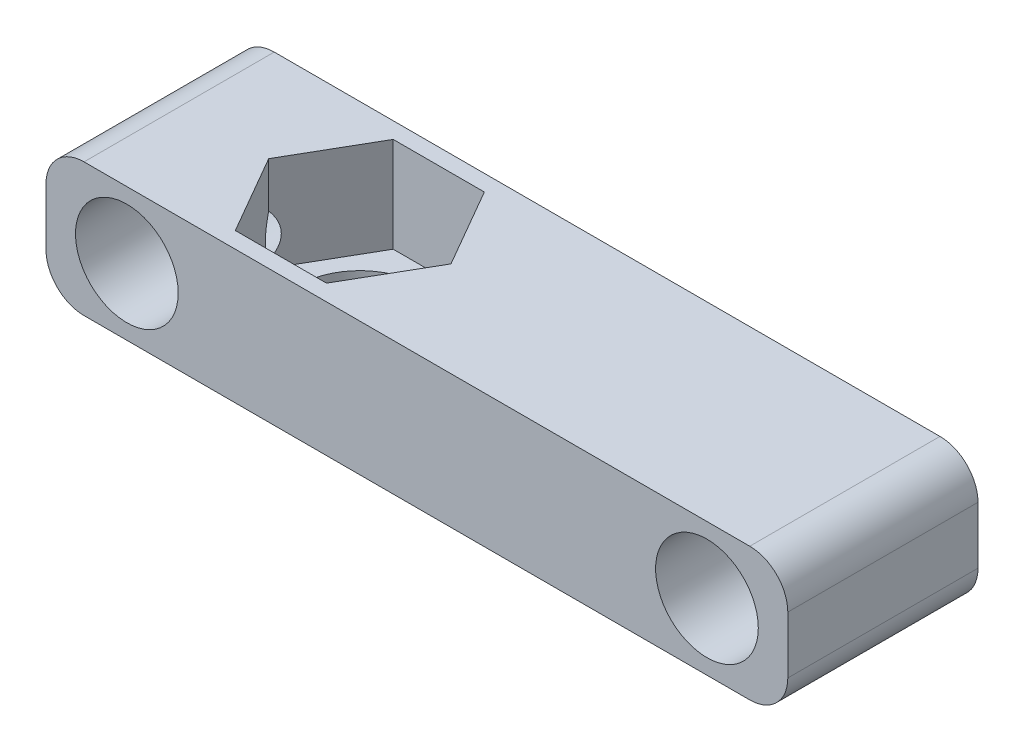
SolidWorks part; units mm, degrees
ref_plane "Alzado" through (0, 0, 0) normal (0, 0, 1) x (1, 0, 0)
ref_plane "Planta" through (0, 0, 0) normal (0, 1, 0) x (1, 0, 0)
ref_plane "Vista lateral" through (0, 0, 0) normal (1, 0, 0) x (0, 0, -1)
sketch "Croquis1" plane through (0, 0, 0) normal (0, 0, 1) x (1, 0, 0)
  line L1 (-46.0167, 15.878) -> (-7.0167, 15.878)
  line L2 (-46.0167, 15.878) -> (-46.0167, 8.878)
  line L3 (-46.0167, 8.878) -> (-7.0167, 8.878)
  line L4 (-7.0167, 15.878) -> (-7.0167, 8.878)
  circle A0 centre (-41.7667, 12.378) radius 2.7
  circle A1 centre (-11.2667, 12.378) radius 2.7
  dimension "D5" = 2
  dimension "D6" = 4.25
  dimension "D7" = 5.4
  dimension "D1" = 39
  dimension "D2" = 7
  dimension "D3" = 4.25
  dimension "D4" = 3.5
extrude "Saliente-Extruir1" add sketch "Croquis1" along normal blind 10
sketch "Croquis2" plane through (0, 8.878, 0) normal (0, -1, 0) x (1, 0, 0)
  line L0 (-46.0167, 10) -> (-7.0167, 10) construction
  line L1 (-46.0167, 10) -> (-46.0167, 0) construction
  line L3 (-29.7247, 5) -> (-32.1207, 9.15)
  line L4 (-32.1207, 9.15) -> (-36.9127, 9.15)
  line L5 (-36.9127, 9.15) -> (-39.3087, 5)
  line L6 (-39.3087, 5) -> (-36.9127, 0.85)
  line L7 (-36.9127, 0.85) -> (-32.1207, 0.85)
  line L8 (-32.1207, 0.85) -> (-29.7247, 5)
  circle A1 centre (-34.5167, 5) radius 4.15 construction
  dimension "D1" = 5
  dimension "D3" = 8.3
  dimension "D2" = 11.5
extrude "Cortar-Extruir1" cut sketch "Croquis2" against normal up to vertex (7 mm away)
sketch "Croquis4" plane through (0, 8.878, 0) normal (0, -1, 0) x (1, 0, 0)
  line L0 (-39.3087, 5) -> (-40.3087, 5) construction
  line L1 (-29.7247, 5) -> (-32.1207, 9.15)
  line L2 (-32.1207, 9.15) -> (-36.9127, 9.15)
  line L3 (-36.9127, 9.15) -> (-39.3087, 5)
  line L4 (-39.3087, 5) -> (-36.9127, 0.85)
  line L5 (-36.9127, 0.85) -> (-32.1207, 0.85)
  line L6 (-32.1207, 0.85) -> (-29.7247, 5)
  circle A0 centre (-34.5167, 5) radius 3.25
  circle A1 centre (-34.5167, 5) radius 4.15 construction
  dimension "D2" = 8.3
fillet "Redondeo1" radius 2 4 edges at (-7.0167, 15.878, 5) (-7.0167, 8.878, 5) (-46.0167, 8.878, 5) (-46.0167, 15.878, 5)
extrude "Saliente-Extruir2" add sketch "Croquis4" against normal blind 2
